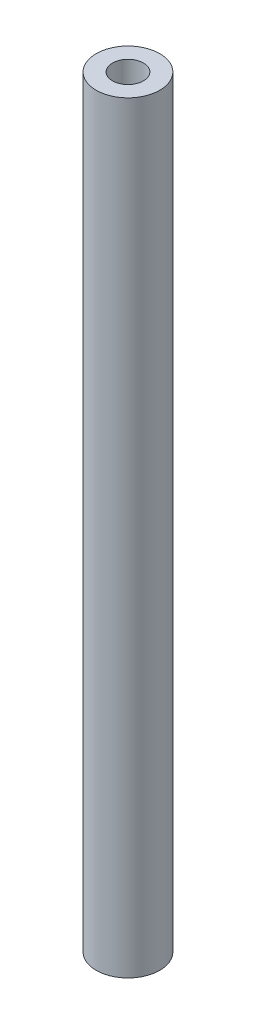
SolidWorks part; units mm, degrees
material "Copper"
ref_plane "Front Plane" through (0, 0, 0) normal (0, 0, 1) x (1, 0, 0)
ref_plane "Top Plane" through (0, 0, 0) normal (0, 1, 0) x (1, 0, 0)
ref_plane "Right Plane" through (0, 0, 0) normal (1, 0, 0) x (0, 0, -1)
sketch "Sketch1" plane through (0, 0, 0) normal (0, 1, 0) x (1, 0, 0)
  circle A0 centre (0, 0) radius 0.7747
  circle A1 centre (0, 0) radius 1.5875
  dimension "D1" = 1.5494
  dimension "D2" = 3.175
extrude "Boss-Extrude1" add sketch "Sketch1" against normal blind 38.1
